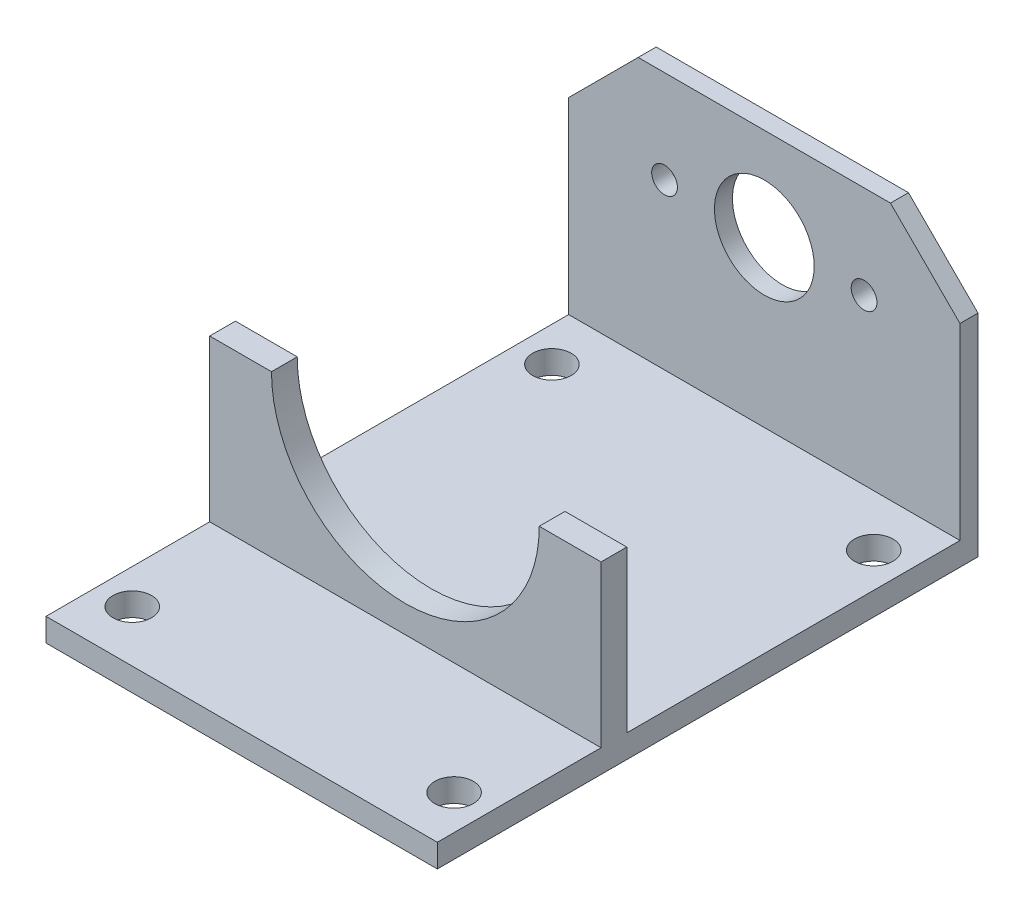
SolidWorks part; units mm, degrees
ref_plane "Front Plane" through (0, 0, 0) normal (0, 0, 1) x (1, 0, 0)
ref_plane "Top Plane" through (0, 0, 0) normal (0, 1, 0) x (1, 0, 0)
ref_plane "Right Plane" through (0, 0, 0) normal (1, 0, 0) x (0, 0, -1)
sketch "Sketch1" plane through (0, 0, 0) normal (0, 1, 0) x (1, 0, 0)
  line L1 (-15.2, 21) -> (15.2, 21)
  line L2 (-15.2, 21) -> (-15.2, -21)
  line L3 (-15.2, -21) -> (15.2, -21)
  line L4 (15.2, 21) -> (15.2, -21)
  line L5 (-15.2, 21) -> (15.2, -21) construction
  line L6 (-15.2, -21) -> (15.2, 21) construction
  point P0 (0, 0)
  dimension "D1" = 30.4
  dimension "D2" = 42
extrude "Boss-Extrude1" add sketch "Sketch1" along normal blind 1.8
sketch "Sketch2" plane through (0, 1.8, 0) normal (0, 1, 0) x (1, 0, 0)
  line L0 (15.2, -21) -> (15.2, 21) construction
  line L1 (-15.2, 21) -> (15.2, 21)
  line L2 (-15.2, 21) -> (-15.2, 19.6)
  line L3 (-15.2, 19.6) -> (15.2, 19.6)
  line L4 (15.2, 21) -> (15.2, 19.6)
  dimension "D1" = 1.4
extrude "Boss-Extrude2" add sketch "Sketch2" along normal blind 20
sketch "Sketch3" plane through (0, 1.8, 0) normal (0, 1, 0) x (1, 0, 0)
  line L0 (11, 15.6) -> (15.2, 15.6) construction
  line L1 (15.2, -21) -> (15.2, 19.6) construction
  line L2 (-11, 15.6) -> (-14, 15.6) construction
  line L4 (-15.2, 19.6) -> (15.2, 19.6) construction
  line L5 (-11, 15.6) -> (11, 15.6) construction
  line L6 (-12.5, 15.6) -> (-12.5, 14.1) construction
  line L7 (-12.5, -17) -> (12.5, -17) construction
  line L8 (-12.5, -15.5) -> (-12.5, -17) construction
  line L9 (-15.2, -21) -> (15.2, -21) construction
  circle A0 centre (12.5, 15.6) radius 1.5
  circle A1 centre (-12.5, 15.6) radius 1.5
  circle A2 centre (-12.5, -17) radius 1.5
  circle A3 centre (12.5, -17) radius 1.5
  dimension "D1" = 3
  dimension "D2" = 3
  dimension "D3" = 2.7
  dimension "D4" = 4
  dimension "D5" = 4
extrude "Cut-Extrude1" cut sketch "Sketch3" against normal blind 20
sketch "Sketch4" plane through (0, 0, -19.6) normal (0, 0, 1) x (1, 0, 0)
  line L0 (-15.2, 16.4) -> (-9.8, 21.8)
  line L1 (-15.2, 21.8) -> (-15.2, 1.8) construction
  line L2 (-15.2, 21.8) -> (15.2, 21.8) construction
  line L3 (-9.8, 21.8) -> (-15.2, 21.8)
  line L4 (-15.2, 21.8) -> (-15.2, 16.4)
  line L6 (15.2, 21.8) -> (15.2, 1.8) construction
  line L7 (15.2, 16.4) -> (15.2, 21.8)
  line L8 (15.2, 21.8) -> (9.8, 21.8)
  line L9 (9.8, 21.8) -> (15.2, 16.4)
  line L10 (0, 21.8) -> (0, 1.8) construction
  line L11 (-15.2, 1.8) -> (15.2, 1.8) construction
  line L12 (0, 14.58) -> (-15.2, 14.58) construction
  line L13 (-15.2, 14.58) -> (15.2, 14.58) construction
  circle A0 centre (0, 14.58) radius 3.875
  circle A1 centre (-7.75, 14.58) radius 1
  circle A2 centre (7.75, 14.58) radius 1
  dimension "D7" = 2
  dimension "D8" = 2
  dimension "D9" = 7.75
  dimension "D1" = 5.4
  dimension "D2" = 5.4
  dimension "D3" = 5.4
  dimension "D4" = 7.22
  dimension "D5" = 7.75
  dimension "D6" = 7.75
extrude "Cut-Extrude2" cut sketch "Sketch4" against normal blind 20
sketch "Sketch5" plane through (0, 1.8, 0) normal (0, 1, 0) x (1, 0, 0)
  line L0 (15.2, -21) -> (15.2, 19.6) construction
  line L1 (15.2, -8.2837) -> (-15.2, -8.2837)
  line L2 (15.2, -8.2837) -> (15.2, -6.2837)
  line L3 (15.2, -6.2837) -> (-15.2, -6.2837)
  line L4 (-15.2, -8.2837) -> (-15.2, -6.2837)
  line L5 (-15.2, 19.6) -> (-15.2, -21) construction
  dimension "D1" = 2
extrude "Boss-Extrude3" add sketch "Sketch5" along normal blind 12.5
sketch "Sketch6" plane through (0, 0, 8.2837) normal (0, 0, 1) x (1, 0, 0)
  line L0 (-15.2, 14.3) -> (15.2, 14.3) construction
  circle A0 centre (0, 14.3) radius 10.4
  dimension "D1" = 20.8
extrude "Cut-Extrude3" cut sketch "Sketch6" against normal blind 10
